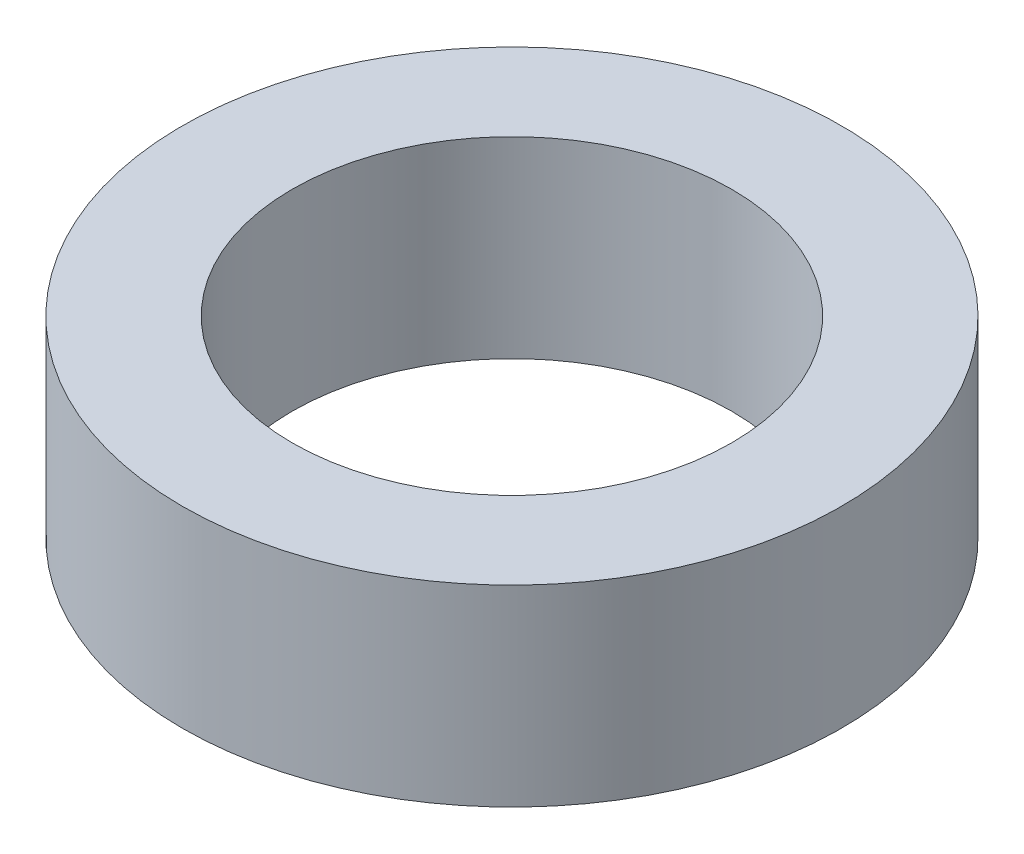
SolidWorks part; units mm, degrees
ref_plane "Front Plane" through (0, 0, 0) normal (0, 0, 1) x (1, 0, 0)
ref_plane "Top Plane" through (0, 0, 0) normal (0, 1, 0) x (1, 0, 0)
ref_plane "Right Plane" through (0, 0, 0) normal (1, 0, 0) x (0, 0, -1)
sketch "Sketch1" plane through (0, 0, 0) normal (0, 1, 0) x (1, 0, 0)
  circle A0 centre (0, 0) radius 12
  circle A2 centre (0, 0) radius 8
  dimension "D1" = 16
  dimension "D2" = 4
extrude "Boss-Extrude1" add sketch "Sketch1" along normal blind 7
